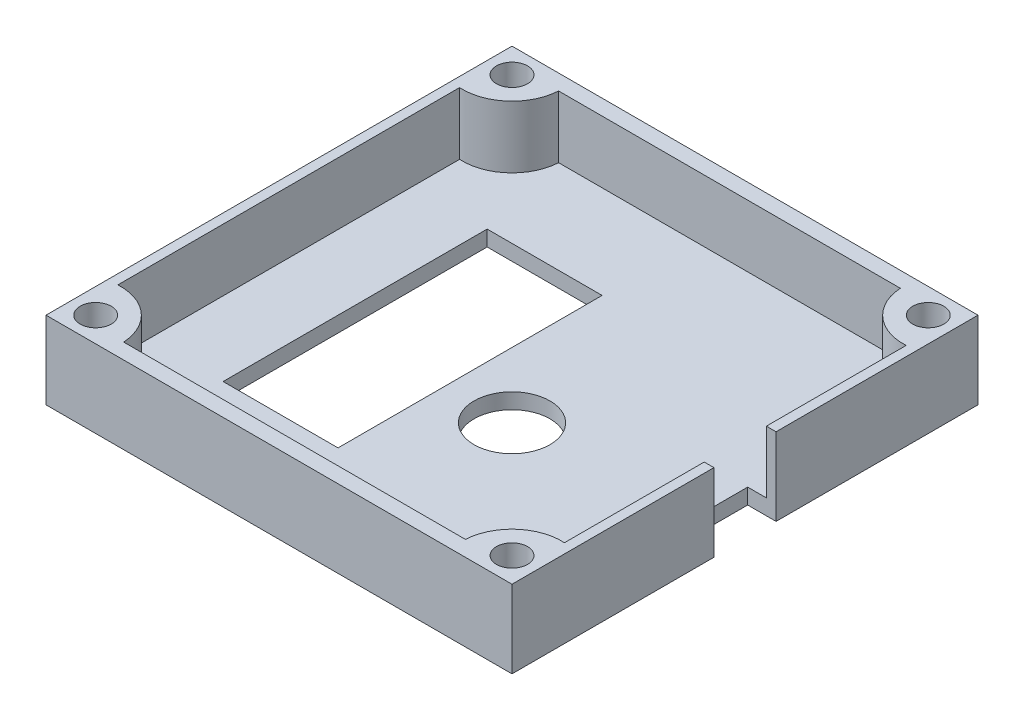
SolidWorks part; units mm, degrees
ref_plane "Front Plane" through (0, 0, 0) normal (0, 0, 1) x (1, 0, 0)
ref_plane "Top Plane" through (0, 0, 0) normal (0, 1, 0) x (1, 0, 0)
ref_plane "Right Plane" through (0, 0, 0) normal (1, 0, 0) x (0, 0, -1)
sketch "Sketch1" plane through (0, 0, 0) normal (0, 1, 0) x (1, 0, 0)
  line L0 (0, 0) -> (0, 6.2274) construction
  line L1 (19.05, -19.05) -> (-19.05, -19.05)
  line L2 (19.05, -19.05) -> (19.05, 19.05)
  line L3 (19.05, 19.05) -> (-19.05, 19.05)
  line L4 (-19.05, -19.05) -> (-19.05, 19.05)
  line L5 (19.05, -19.05) -> (-19.05, 19.05) construction
  line L6 (19.05, 19.05) -> (-19.05, -19.05) construction
  line L7 (0, 0) -> (-5.6561, 0) construction
  circle A0 centre (-17.018, 17.018) radius 1.27
  circle A1 centre (-17.018, -17.018) radius 1.27
  circle A2 centre (17.018, -17.018) radius 1.27
  circle A3 centre (17.018, 17.018) radius 1.27
  point P0 (0, 0)
  dimension "D3" = 2.54
  dimension "D1" = 38.1
  dimension "D2" = 38.1
  dimension "D4" = 2.032
extrude "Boss-Extrude1" add sketch "Sketch1" along normal blind 6.35
sketch "Sketch2" plane through (0, 6.35, 0) normal (0, 1, 0) x (1, 0, 0)
  line L0 (-19.05, 19.05) -> (-19.05, -19.05) construction
  line L1 (-13.97, -17.78) -> (13.97, -17.78)
  line L2 (18.2563, 13.97) -> (18.2563, -13.97)
  line L7 (-17.78, 13.97) -> (-18.2563, 13.97)
  line L9 (-17.78, -13.97) -> (-18.2563, -13.97)
  line L10 (-18.2563, 13.97) -> (-18.2563, -13.97)
  line L11 (19.05, 19.05) -> (-19.05, 19.05) construction
  line L12 (-19.05, -19.05) -> (19.05, -19.05) construction
  line L16 (-13.97, 17.78) -> (13.97, 17.78)
  line L18 (-6.0127, 0) -> (0, 0) construction
  line L19 (0, 0) -> (0, 6.0568) construction
  arc A0 (-18.2563, 13.97) -> (-13.97, 17.78) centre (-18.0181, 18.0181) ccw
  arc A1 (-18.2563, -13.97) -> (-13.97, -17.78) centre (-18.0181, -18.0181) cw
  arc A2 (18.2563, -13.97) -> (13.97, -17.78) centre (18.0181, -18.0181) ccw
  arc A3 (18.2563, 13.97) -> (13.97, 17.78) centre (18.0181, 18.0181) cw
  point P0 (0, 0)
  point P1 (0, 0)
  dimension "D3" = 0.7937
  dimension "D4" = 5.08
  dimension "D5" = 5.08
  dimension "D6" = 1.27
extrude "Cut-Extrude1" cut sketch "Sketch2" against normal blind 5.08 contours L2 A3 L16 A0 L10 A1 L1 A2
sketch "Sketch3" plane through (0, 0, 0) normal (0, -1, 0) x (1, 0, 0)
  line L0 (-19.05, -19.05) -> (-19.05, 19.05) construction
  line L1 (-2.794, -10.16) -> (-12.192, -10.16)
  line L2 (-2.794, -10.16) -> (-2.794, 11.43)
  line L3 (-2.794, 11.43) -> (-12.192, 11.43)
  line L4 (-12.192, -10.16) -> (-12.192, 11.43)
  line L5 (-2.794, -10.16) -> (-12.192, 11.43) construction
  line L6 (-2.794, 11.43) -> (-12.192, -10.16) construction
  line L7 (-19.05, 19.05) -> (19.05, 19.05) construction
  point P0 (-7.493, 0.635)
  dimension "D1" = 21.59
  dimension "D2" = 9.398
  dimension "D3" = 6.858
  dimension "D4" = 7.62
extrude "Cut-Extrude2" cut sketch "Sketch3" against normal up to next
sketch "Sketch4" plane through (0, 0, 0) normal (0, -1, 0) x (1, 0, 0)
  line L0 (-19.05, 19.05) -> (19.05, 19.05) construction
  line L1 (19.05, 19.05) -> (19.05, -19.05) construction
  line L3 (21.3704, -2.54) -> (16.7296, -2.54)
  line L4 (21.3704, -2.54) -> (21.3704, 2.54)
  line L5 (21.3704, 2.54) -> (16.7296, 2.54)
  line L6 (16.7296, -2.54) -> (16.7296, 2.54)
  line L7 (21.3704, -2.54) -> (16.7296, 2.54) construction
  line L8 (21.3704, 2.54) -> (16.7296, -2.54) construction
  circle A0 centre (2.54, 2.54) radius 3.1019
  point P6 (19.05, 0)
  point P11 (0, 0)
  line M7 (19.05, -19.05) -> (19.05, 19.05)
  dimension "D1" = 16.51
  dimension "D2" = 16.51
  dimension "D3" = 16.51
extrude "Cut-Extrude3" cut sketch "Sketch4" against normal through all contours L4 L5 L3 M7 | L6 L3 L5 M7 | A0
